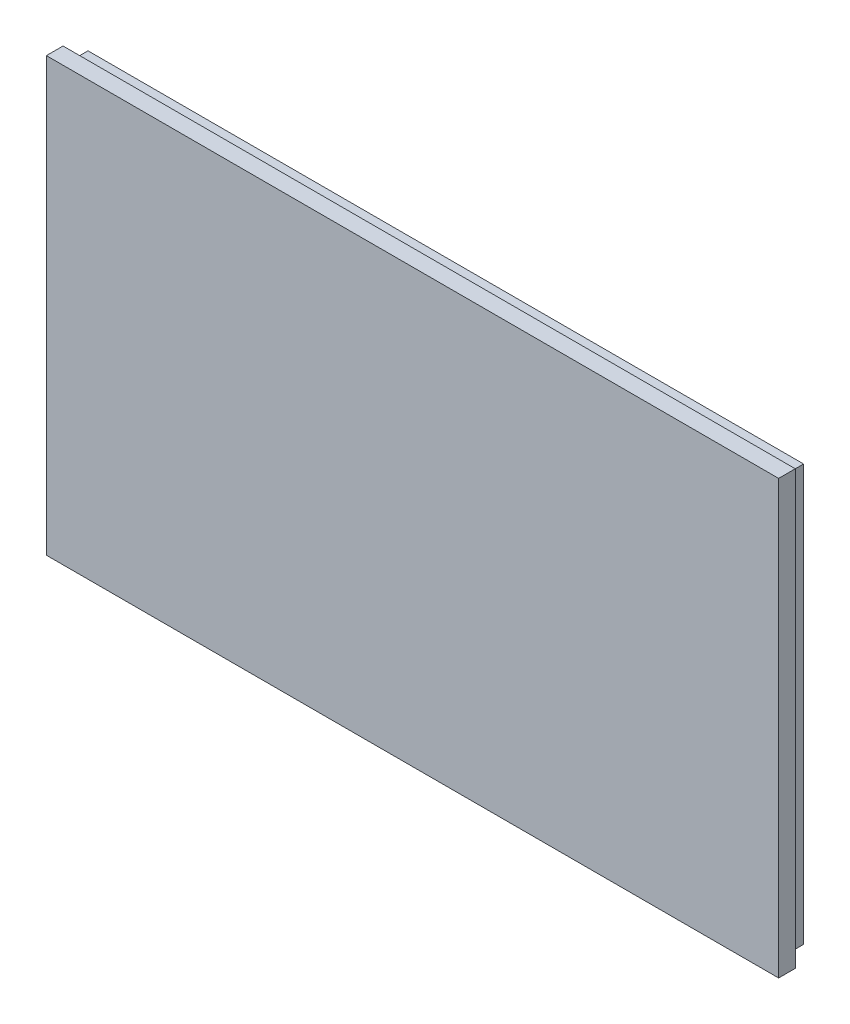
SolidWorks part; units mm, degrees
ref_plane "Front Plane" through (0, 0, 0) normal (0, 0, 1) x (1, 0, 0)
ref_plane "Top Plane" through (0, 0, 0) normal (0, 1, 0) x (1, 0, 0)
ref_plane "Right Plane" through (0, 0, 0) normal (1, 0, 0) x (0, 0, -1)
sketch "Sketch1" plane through (0, 0, 0) normal (0, 0, 1) x (1, 0, 0)
  line L1 (-22, -13) -> (22, -13)
  line L2 (-22, -13) -> (-22, 13)
  line L3 (-22, 13) -> (22, 13)
  line L4 (22, -13) -> (22, 13)
  line L5 (-22, -13) -> (22, 13) construction
  line L6 (-22, 13) -> (22, -13) construction
  point P0 (0, 0)
  dimension "D1" = 44
  dimension "D2" = 26
extrude "Boss-Extrude1" add sketch "Sketch1" along normal blind 1
sketch "Sketch2" plane through (0, 0, 0) normal (0, 0, -1) x (-1, 0, 0)
  line L1 (-21.5, -12.5) -> (21.5, -12.5)
  line L2 (-21.5, -12.5) -> (-21.5, 12.5)
  line L3 (-21.5, 12.5) -> (21.5, 12.5)
  line L4 (21.5, -12.5) -> (21.5, 12.5)
  line L5 (-21.5, -12.5) -> (21.5, 12.5) construction
  line L6 (-21.5, 12.5) -> (21.5, -12.5) construction
  point P0 (0, 0)
  dimension "D1" = 43
  dimension "D2" = 25
extrude "Boss-Extrude2" add sketch "Sketch2" along normal blind 1
